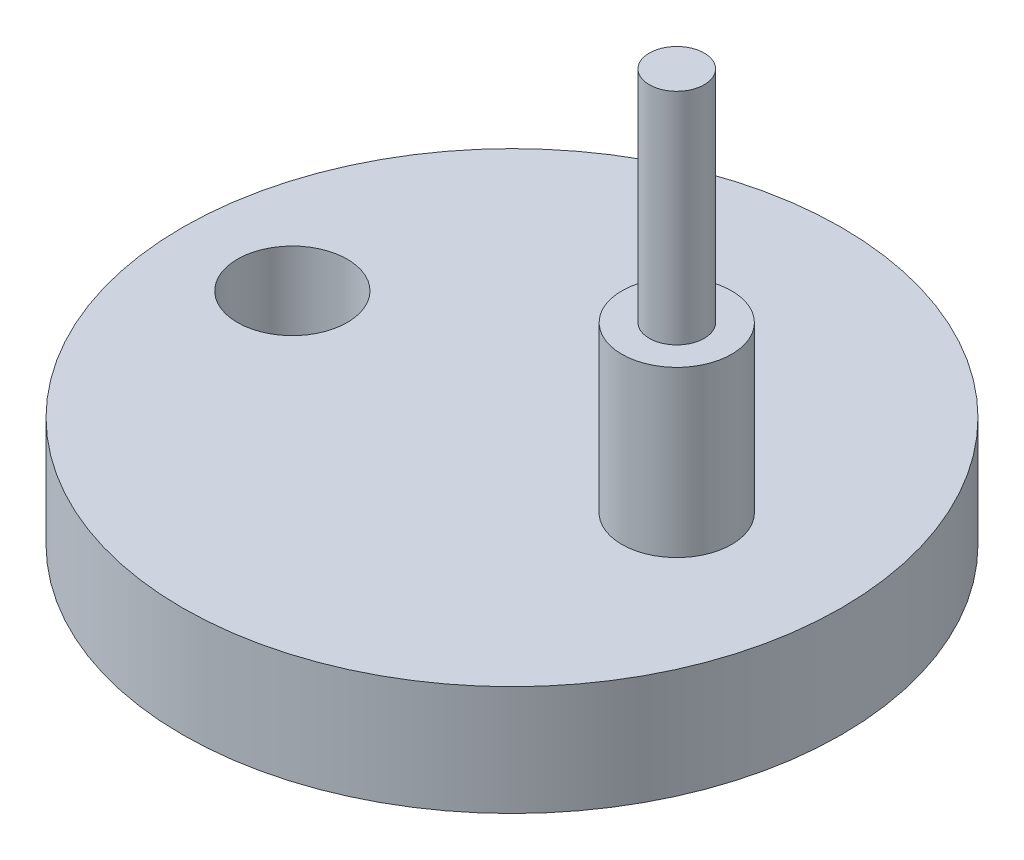
SolidWorks part; units mm, degrees
ref_plane "정면" through (0, 0, 0) normal (0, 0, 1) x (1, 0, 0)
ref_plane "윗면" through (0, 0, 0) normal (0, 1, 0) x (1, 0, 0)
ref_plane "우측면" through (0, 0, 0) normal (1, 0, 0) x (0, 0, -1)
sketch "스케치1" plane through (0, 0, 0) normal (0, 1, 0) x (1, 0, 0)
  circle A0 centre (0, 0) radius 30
  dimension "D1" = 60
extrude "보스-돌출1" add sketch "스케치1" along normal blind 10
sketch "스케치2" plane through (0, 10, 0) normal (0, 1, 0) x (1, 0, 0)
  circle A0 centre (0, 0) radius 15 construction
  circle A1 centre (15, 0) radius 5
  dimension "D1" = 10
  dimension "D2" = 30
extrude "보스-돌출2" add sketch "스케치2" along normal blind 15
sketch "스케치3" plane through (0, 25, 0) normal (0, 1, 0) x (1, 0, 0)
  circle A0 centre (15, 0) radius 2.5
  dimension "D1" = 5
extrude "보스-돌출3" add sketch "스케치3" along normal blind 20
sketch "스케치5" plane through (0, 10, 0) normal (0, 1, 0) x (1, 0, 0)
  circle A0 centre (-20, 0) radius 5
  dimension "D1" = 10
  dimension "D2" = 20
extrude "컷-돌출2" cut sketch "스케치5" against normal blind 100 contours A0
